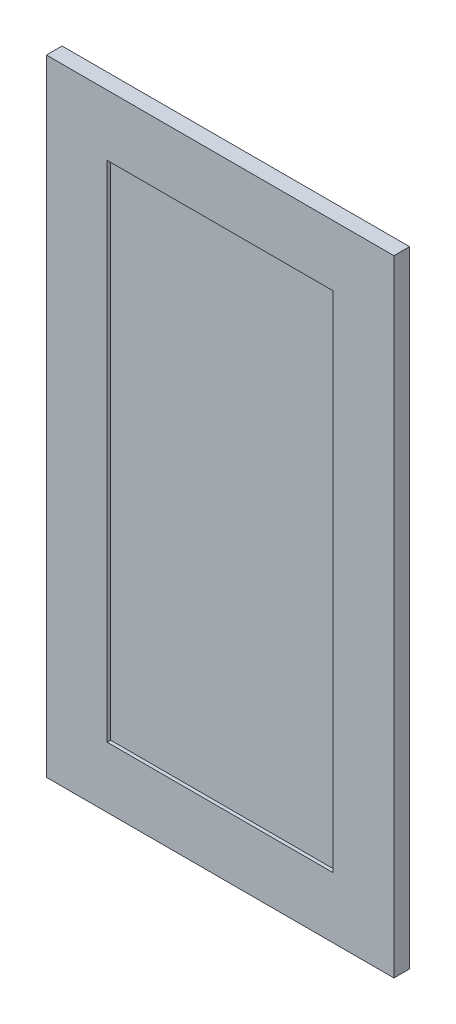
SolidWorks part; units mm, degrees
material "Pine"
ref_plane "Front Plane" through (0, 0, 0) normal (0, 0, 1) x (1, 0, 0)
ref_plane "Top Plane" through (0, 0, 0) normal (0, 1, 0) x (1, 0, 0)
ref_plane "Right Plane" through (0, 0, 0) normal (1, 0, 0) x (0, 0, -1)
sketch "Sketch1" plane through (0, 0, 0) normal (0, 0, 1) x (1, 0, 0)
  line L1 (-200, 360) -> (200, 360)
  line L2 (-200, 360) -> (-200, -360)
  line L3 (-200, -360) -> (200, -360)
  line L4 (200, 360) -> (200, -360)
  line L5 (-200, 360) -> (200, -360) construction
  line L6 (-200, -360) -> (200, 360) construction
  point P0 (0, 0)
  dimension "D1" = 720
  dimension "D2" = 400
extrude "Boss-Extrude1" add sketch "Sketch1" along normal blind 18
sketch "Sketch2" plane through (0, 0, 18) normal (0, 0, 1) x (1, 0, 0)
  line L0 (-200, 360) -> (-200, -360) construction
  line L1 (-130, 290) -> (130, 290)
  line L2 (-130, 290) -> (-130, -290)
  line L3 (-130, -290) -> (130, -290)
  line L4 (130, 290) -> (130, -290)
  line L5 (-130, 290) -> (130, -290) construction
  line L6 (-130, -290) -> (130, 290) construction
  line L7 (200, 360) -> (-200, 360) construction
  point P0 (0, 0)
  dimension "D1" = 70
  dimension "D2" = 70
extrude "Cut-Extrude1" cut sketch "Sketch2" against normal blind 4
